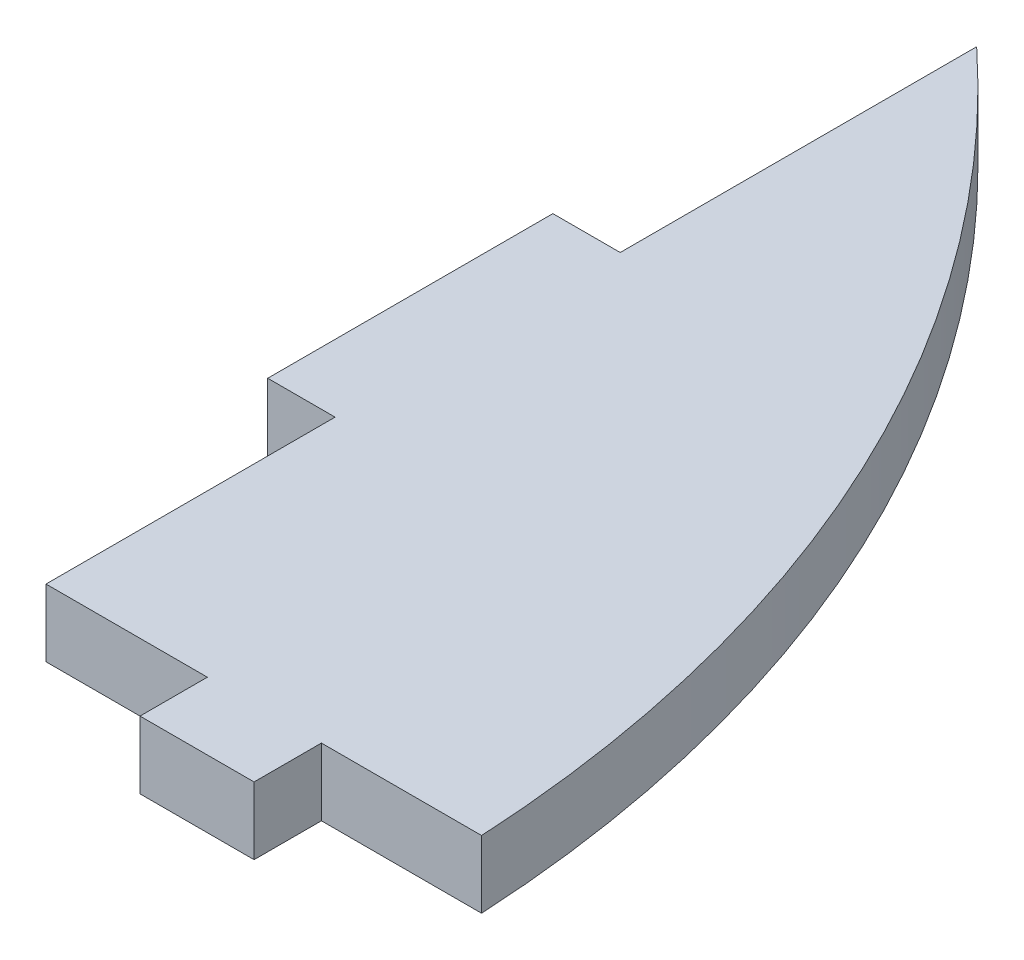
SolidWorks part; units mm, degrees
ref_plane "Front Plane" through (0, 0, 0) normal (0, 0, 1) x (1, 0, 0)
ref_plane "Top Plane" through (0, 0, 0) normal (0, 1, 0) x (1, 0, 0)
ref_plane "Right Plane" through (0, 0, 0) normal (1, 0, 0) x (0, 0, -1)
sketch "Sketch2" plane through (0, 0, 0) normal (0, 1, 0) x (1, 0, 0)
  line L0 (0, 0) -> (0, 12.875)
  line L1 (0, 0) -> (7.1867, 0)
  line L2 (0, 25.575) -> (0, 41.45)
  line L3 (0, 12.875) -> (-3, 12.875)
  line L4 (0, 25.575) -> (0, 12.875) construction
  line L5 (0, 25.575) -> (-3, 25.575)
  line L6 (-3, 12.875) -> (-3, 25.575)
  line L7 (0, 19.225) -> (-3, 25.575) construction
  line L8 (0, 19.225) -> (-3, 12.875) construction
  line L9 (9.7267, 0) -> (9.7267, -3) construction
  line L10 (7.1867, 0) -> (12.2667, 0) construction
  line L11 (7.1867, 0) -> (7.1867, -3)
  line L12 (7.1867, -3) -> (12.2667, -3)
  line L13 (12.2667, 0) -> (12.2667, -3)
  line L14 (12.2667, 0) -> (19.4, 0)
  arc A0 (0, 41.45) -> (19.4, 0) centre (-41.4746, -3.2264) cw
  point P5 (0, 19.225)
  point P15 (9.7267, 0)
  dimension "D3" = 60.96
  dimension "D1" = 19.4
  dimension "D2" = 41.45
  dimension "D4" = 3
  dimension "D5" = 12.7
  dimension "D6" = 12.875
  dimension "D7" = 5.08
  dimension "D8" = 3
extrude "Boss-Extrude1" add sketch "Sketch2" along normal blind 3
